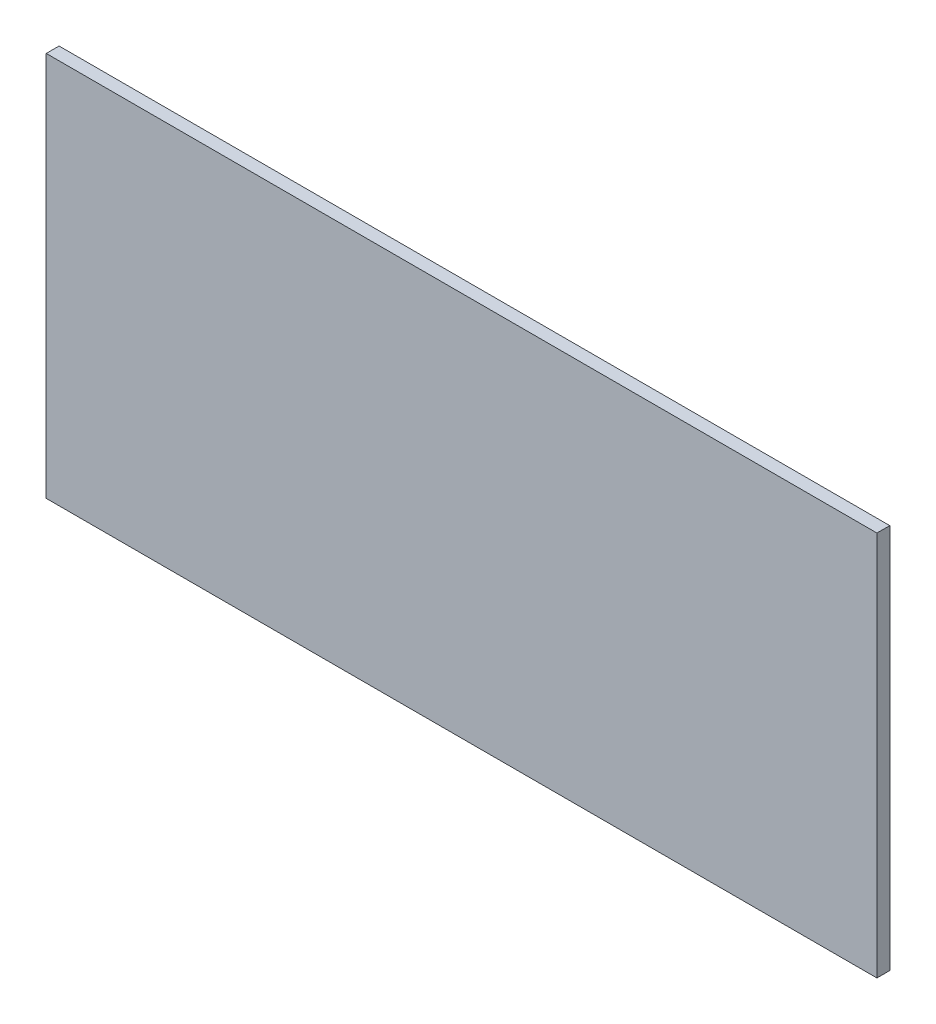
SolidWorks part; units mm, degrees
ref_plane "前基準面" through (0, 0, 0) normal (0, 0, 1) x (1, 0, 0)
ref_plane "上基準面" through (0, 0, 0) normal (0, 1, 0) x (1, 0, 0)
ref_plane "右基準面" through (0, 0, 0) normal (1, 0, 0) x (0, 0, -1)
sketch "草圖1" plane through (0, 0, 0) normal (0, 0, 1) x (1, 0, 0)
  line L1 (-100, 45) -> (94, 45)
  line L2 (-100, 45) -> (-100, -45)
  line L3 (-100, -45) -> (94, -45)
  line L4 (94, 45) -> (94, -45)
  dimension "D1" = 194
  dimension "D2" = 90
extrude "填料-伸長1" add sketch "草圖1" along normal blind 3
